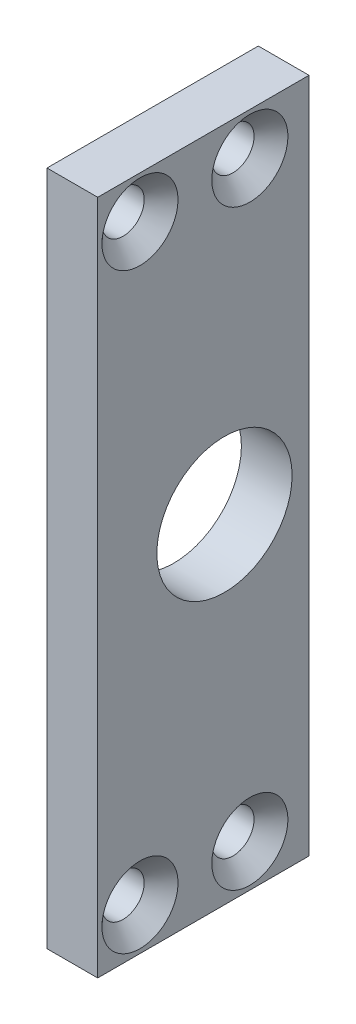
SolidWorks part; units mm, degrees
ref_plane "Plan de face" through (0, 0, 0) normal (0, 0, 1) x (1, 0, 0)
ref_plane "Plan de dessus" through (0, 0, 0) normal (0, 1, 0) x (1, 0, 0)
ref_plane "Plan de droite" through (0, 0, 0) normal (1, 0, 0) x (0, 0, -1)
sketch "Esquisse1" plane through (0, 0, 0) normal (1, 0, 0) x (0, 0, -1)
  line L1 (0, 0) -> (25, 0)
  line L2 (0, 0) -> (0, 80)
  line L3 (0, 80) -> (25, 80)
  line L4 (25, 0) -> (25, 80)
  dimension "D1" = 25
  dimension "D2" = 80
extrude "Extrusion1" add sketch "Esquisse1" along normal blind 6
sketch "Esquisse2" plane through (6, 0, 0) normal (1, 0, 0) x (0, 0, -1)
  line L0 (25, 0) -> (25, 80) construction
  line L1 (25, 80) -> (0, 80) construction
  line L2 (0, 80) -> (0, 0) construction
  line L3 (0, 0) -> (25, 0) construction
  circle A0 centre (15, 40) radius 8
  circle A1 centre (5, 5) radius 2.5
  circle A2 centre (18, 5) radius 2.5
  circle A3 centre (5, 75) radius 2.5
  circle A4 centre (18, 75) radius 2.5
  dimension "D1" = 16
  dimension "D2" = 10
  dimension "D3" = 40
  dimension "D4" = 5
  dimension "D5" = 5
  dimension "D6" = 5
extrude "Extrusion2" cut sketch "Esquisse2" against normal through all
chamfer "Chanfrein1" distance 2 angle 45 4 edges at (6, 5, -7.5) (6, 5, -20.5) (6, 75, -20.5) (6, 75, -7.5)
